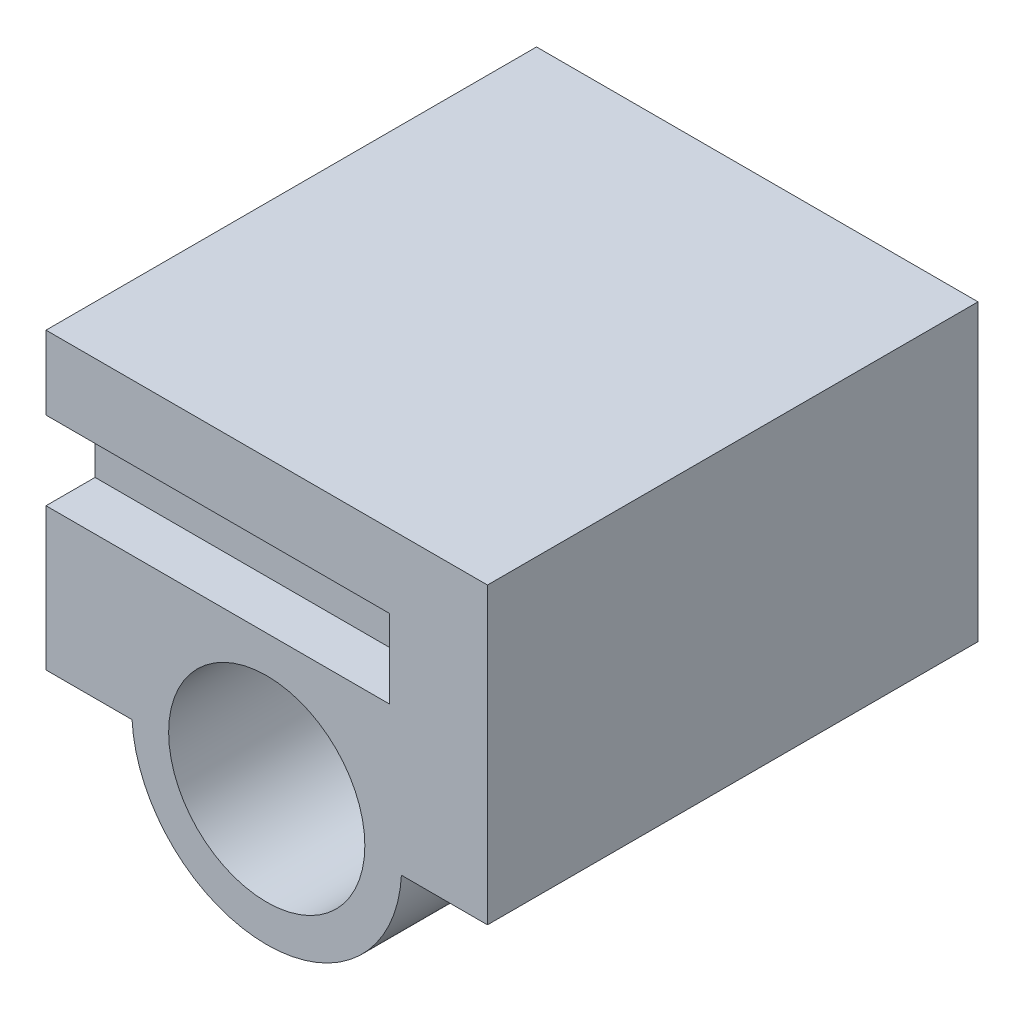
SolidWorks part; units mm, degrees
ref_plane "Front Plane" through (0, 0, 0) normal (0, 0, 1) x (1, 0, 0)
ref_plane "Top Plane" through (0, 0, 0) normal (0, 1, 0) x (1, 0, 0)
ref_plane "Right Plane" through (0, 0, 0) normal (1, 0, 0) x (0, 0, -1)
sketch "Sketch1" plane through (0, 0, 0) normal (0, 0, 1) x (1, 0, 0)
  line L1 (-4.5, 3) -> (4.5, 3)
  line L2 (-4.5, 3) -> (-4.5, -3)
  line L3 (-4.5, -3) -> (4.5, -3)
  line L4 (4.5, 3) -> (4.5, -3)
  line L5 (-4.5, 3) -> (4.5, -3) construction
  line L6 (-4.5, -3) -> (4.5, 3) construction
  point P0 (0, 0)
  dimension "D1" = 9
  dimension "D2" = 6
extrude "Boss-Extrude1" add sketch "Sketch1" along normal blind 10
sketch "Sketch2" plane through (4.5, 0, 0) normal (1, 0, 0) x (0, 0, -1)
  line L0 (-10, -3) -> (-10, 3) construction
  line L1 (-10, 1.5) -> (0, 1.5)
  line L2 (-10, 1.5) -> (-10, -0.1)
  line L3 (-10, -0.1) -> (0, -0.1)
  line L4 (0, 1.5) -> (0, -0.1)
  line L5 (0, -3) -> (0, 3) construction
  line L6 (-10, 3) -> (0, 3) construction
  dimension "D1" = 1.6
  dimension "D2" = 1.5
extrude "Cut-Extrude1" cut sketch "Sketch2" against normal blind 7 from offset 2 offset against normal yes
sketch "Sketch3" plane through (0, 0, 10) normal (0, 0, 1) x (1, 0, 0)
  line L0 (0, 0) -> (0, -3) construction
  line L1 (-4.5, -3) -> (4.5, -3) construction
  line L3 (-4.5, -0.1) -> (2.5, -0.1) construction
  circle A0 centre (0, -2.85) radius 2.75
  dimension "D1" = 5.5
  dimension "D2" = 2.75
extrude "Boss-Extrude2" add sketch "Sketch3" against normal through all
sketch "Sketch4" plane through (0, 0, 10) normal (0, 0, 1) x (1, 0, 0)
  circle A0 centre (0, -2.85) radius 2
  arc A1 (-2.7459, -3) -> (2.7459, -3) centre (0, -2.85) ccw construction
  dimension "D1" = 4
extrude "Cut-Extrude2" cut sketch "Sketch4" against normal blind 4
sketch "Sketch5" plane through (-4.5, 0, 0) normal (-1, 0, 0) x (0, 0, 1)
  line L0 (10, -0.1) -> (0, -0.1) construction
  line L2 (0, -0.1) -> (1, -0.1)
  line L3 (0, -0.1) -> (0, 0.65)
  line L4 (0.15, 0.8) -> (0.85, 0.8)
  line L5 (1, -0.1) -> (1, 0.65)
  line L6 (0, -0.1) -> (0, 1.5) construction
  line L7 (2, -0.1) -> (2, 0.65)
  line L8 (2.15, 0.8) -> (2.85, 0.8)
  line L9 (3, -0.1) -> (3, 0.65)
  line L10 (2, -0.1) -> (3, -0.1)
  line L11 (4, -0.1) -> (4, 0.65)
  line L12 (4.15, 0.8) -> (4.85, 0.8)
  line L13 (5, -0.1) -> (5, 0.65)
  line L14 (4, -0.1) -> (5, -0.1)
  line L15 (6, -0.1) -> (6, 0.65)
  line L16 (6.15, 0.8) -> (6.85, 0.8)
  line L17 (7, -0.1) -> (7, 0.65)
  line L18 (6, -0.1) -> (7, -0.1)
  line L19 (8, -0.1) -> (8, 0.65)
  line L20 (8.15, 0.8) -> (8.85, 0.8)
  line L21 (9, -0.1) -> (9, 0.65)
  line L22 (8, -0.1) -> (9, -0.1)
  arc A0 (0, 0.65) -> (0.15, 0.8) centre (0.15, 0.65) cw
  arc A1 (0.85, 0.8) -> (1, 0.65) centre (0.85, 0.65) cw
  arc A2 (2, 0.65) -> (2.15, 0.8) centre (2.15, 0.65) cw
  arc A3 (2.85, 0.8) -> (3, 0.65) centre (2.85, 0.65) cw
  arc A4 (4, 0.65) -> (4.15, 0.8) centre (4.15, 0.65) cw
  arc A5 (4.85, 0.8) -> (5, 0.65) centre (4.85, 0.65) cw
  arc A6 (6, 0.65) -> (6.15, 0.8) centre (6.15, 0.65) cw
  arc A7 (6.85, 0.8) -> (7, 0.65) centre (6.85, 0.65) cw
  arc A8 (8, 0.65) -> (8.15, 0.8) centre (8.15, 0.65) cw
  arc A9 (8.85, 0.8) -> (9, 0.65) centre (8.85, 0.65) cw
  point P8 (0, 0.8)
  point P11 (1, 0.8)
  dimension "D2" = 0.15
  dimension "D1" = 1
  dimension "D3" = 0.75
  dimension "D4" = 0
  dimension "D5" = 5
extrude "Boss-Extrude3" add sketch "Sketch5" against normal up to next
